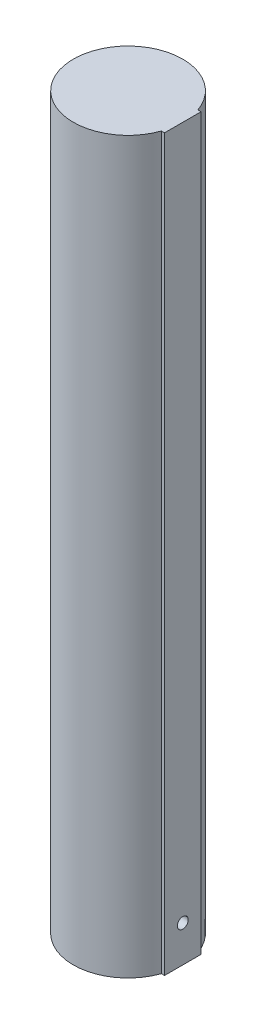
SolidWorks part; units mm, degrees
ref_plane "Front" through (0, 0, 0) normal (0, 0, 1) x (1, 0, 0)
ref_plane "Top" through (0, 0, 0) normal (0, 1, 0) x (1, 0, 0)
ref_plane "Right" through (0, 0, 0) normal (1, 0, 0) x (0, 0, -1)
sketch "Sketch1" plane through (0, 0, 0) normal (0, 1, 0) x (1, 0, 0)
  circle A0 centre (0, 0) radius 15
  dimension "D1" = 30
extrude "Boss-Extrude1" add sketch "Sketch1" along normal blind 200
sketch "Sketch2" plane through (0, 200, 0) normal (0, 1, 0) x (1, 0, 0)
  line L1 (14.1421, 5) -> (15, 5)
  line L2 (14.1421, 5) -> (14.1421, -5)
  line L3 (14.1421, -5) -> (15, -5)
  line L4 (15, 5) -> (15, -5)
  circle A0 centre (0, 0) radius 15 construction
  point P6 (14.0605, -5.2251)
  dimension "D1" = 10
extrude "Boss-Extrude2" add sketch "Sketch2" against normal blind 200
sketch "Sketch3" plane through (0, 0, 0) normal (0, -1, 0) x (1, 0, 0)
  line L0 (1.5, -1.3229) -> (1.5, 1.3229)
  arc A0 (1.5, 1.3229) -> (1.5, -1.3229) centre (0, 0) ccw
  dimension "D1" = 4
  dimension "D2" = 1.5
extrude "Cut-Extrude1" cut sketch "Sketch3" against normal blind 25
sketch "Sketch4" plane through (15, 0, 0) normal (1, 0, 0) x (0, 0, -1)
  line L0 (0, 10) -> (0, 0) construction
  circle A0 centre (0, 10) radius 1.5
  dimension "D2" = 3
  dimension "D1" = 10
extrude "Cut-Extrude2" cut sketch "Sketch4" against normal blind 15
